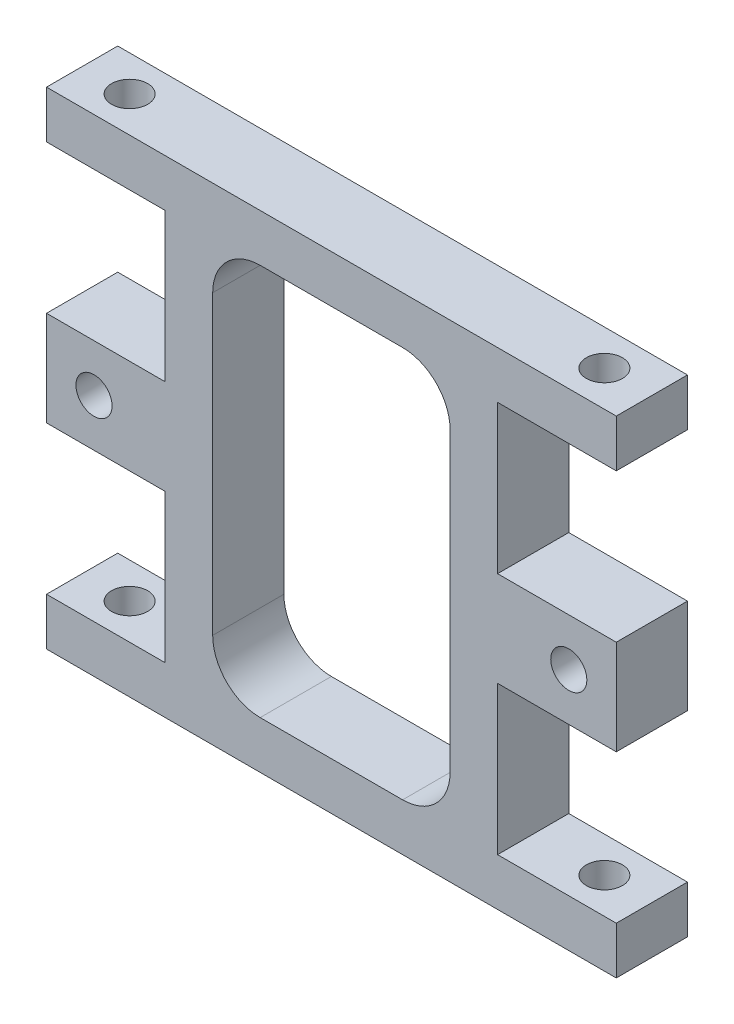
SolidWorks part; units mm, degrees
material "Nylon 6/10"
ref_plane "Front" through (0, 0, 0) normal (0, 0, 1) x (1, 0, 0)
ref_plane "Top" through (0, 0, 0) normal (0, 1, 0) x (1, 0, 0)
ref_plane "Right" through (0, 0, 0) normal (1, 0, 0) x (0, 0, -1)
sketch "Sketch2" plane through (0, 0, 0) normal (0, 0, 1) x (1, 0, 0)
  line L0 (-15.875, 26.1938) -> (15.875, -26.1937) construction
  line L1 (-15.875, -26.1938) -> (15.875, 26.1938) construction
  line L2 (-22.225, -26.1937) -> (-22.225, -6.35)
  line L3 (-38.1, 32.5438) -> (38.1, 32.5438)
  line L4 (22.225, -26.1937) -> (22.225, -6.35)
  line L5 (-15.875, -26.1937) -> (15.875, -26.1937)
  line L6 (-22.225, 6.35) -> (-22.225, 26.1938)
  line L7 (-15.875, 26.1938) -> (15.875, 26.1938)
  line L8 (-15.875, 26.1938) -> (-15.875, -26.1937)
  line L9 (22.225, 6.35) -> (38.1, 6.35)
  line L10 (15.875, 26.1938) -> (15.875, -26.1937)
  line L11 (22.225, -26.1937) -> (38.1, -26.1937)
  line L13 (-38.1, -32.5437) -> (38.1, -32.5437)
  line L14 (38.1, -26.1937) -> (38.1, -32.5437)
  line L15 (-22.225, -26.1937) -> (-38.1, -26.1937)
  line L16 (22.225, -6.35) -> (38.1, -6.35)
  line L17 (38.1, 6.35) -> (38.1, -6.35)
  line L18 (-38.1, -26.1937) -> (-38.1, -32.5437)
  line L19 (-22.225, 6.35) -> (-38.1, 6.35)
  line L20 (22.225, 6.35) -> (22.225, 26.1938)
  line L21 (22.225, 26.1938) -> (38.1, 26.1938)
  line L22 (38.1, 32.5438) -> (38.1, 26.1938)
  line L23 (-22.225, -6.35) -> (-38.1, -6.35)
  line L24 (-38.1, 6.35) -> (-38.1, -6.35)
  line L25 (-22.225, 26.1938) -> (-38.1, 26.1938)
  line L26 (-38.1, 32.5438) -> (-38.1, 26.1938)
  circle A0 centre (-31.75, 0) radius 2.413
  circle A1 centre (31.75, 0) radius 2.413
  point P0 (0, 0)
  point P3 (0, 0)
  point P4 (0, 0)
  point P29 (38.1, 0)
  point P30 (-38.1, 0)
  dimension "D16" = 4.826
  dimension "D17" = 4.826
  dimension "D18" = 6.35
  dimension "D19" = 6.35
  dimension "D1" = 31.75
  dimension "D2" = 6.35
  dimension "D3" = 6.35
  dimension "D4" = 52.3875
  dimension "D5" = 6.35
  dimension "D6" = 15.875
  dimension "D7" = 15.875
  dimension "D8" = 15.875
  dimension "D9" = 6.35
  dimension "D10" = 6.35
  dimension "D11" = 15.875
  dimension "D12" = 15.875
  dimension "D13" = 15.875
  dimension "D14" = 12.7
  dimension "D15" = 12.7
extrude "Boss-Extrude1" add sketch "Sketch2" along normal blind 9.525
fillet "Fillet1" radius 6.35 4 edges at (15.875, 26.1938, 4.7625) (-15.875, 26.1938, 4.7625) (15.875, -26.1937, 4.7625) (-15.875, -26.1937, 4.7625)
sketch "Sketch3" plane through (0, 32.5438, 0) normal (0, 1, 0) x (1, 0, 0)
  line L0 (38.1, 0) -> (-38.1, 0) construction
  line L1 (-38.1, -9.525) -> (-38.1, 0) construction
  line L2 (38.1, -9.525) -> (38.1, 0) construction
  circle A0 centre (-31.75, -4.7625) radius 2.413
  circle A1 centre (31.75, -4.7625) radius 2.413
  dimension "D1" = 4.826
  dimension "D2" = 4.826
  dimension "D3" = 4.7625
  dimension "D4" = 4.7625
  dimension "D5" = 6.35
  dimension "D6" = 6.35
extrude "Cut-Extrude1" cut sketch "Sketch3" against normal up to next
sketch "Sketch4" plane through (0, -32.5437, 0) normal (0, -1, 0) x (1, 0, 0)
  line L0 (-38.1, 9.525) -> (-38.1, 0) construction
  line L1 (38.1, 9.525) -> (38.1, 0) construction
  line L2 (-38.1, 9.525) -> (38.1, 9.525) construction
  circle A0 centre (-31.75, 4.7625) radius 2.413
  circle A1 centre (31.75, 4.7625) radius 2.413
  dimension "D1" = 4.826
  dimension "D2" = 6.35
  dimension "D3" = 4.826
  dimension "D4" = 6.35
  dimension "D5" = 4.7625
  dimension "D6" = 4.7625
extrude "Cut-Extrude2" cut sketch "Sketch4" against normal up to next
